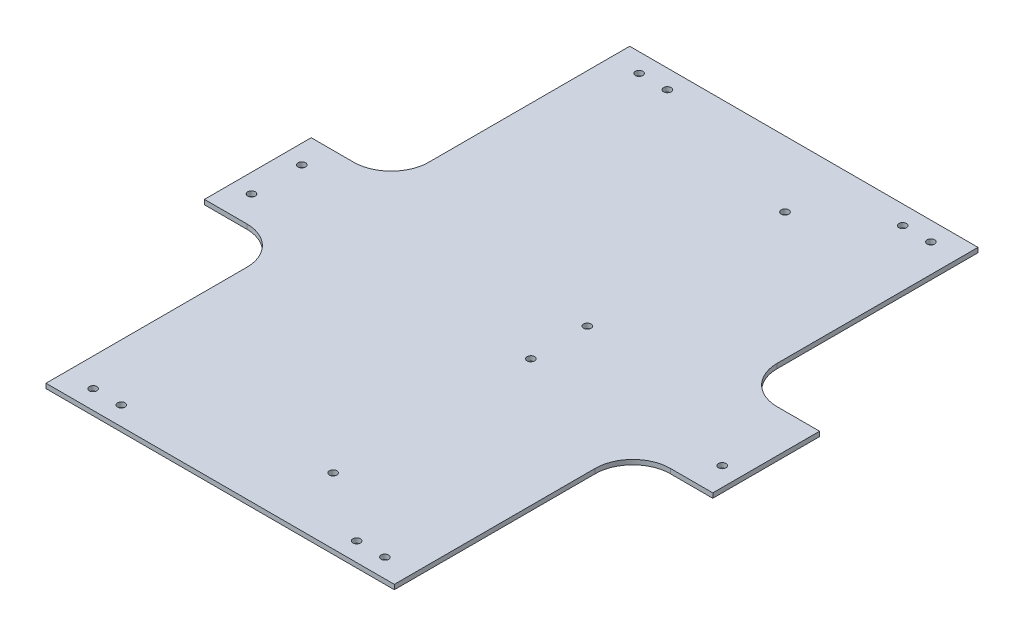
SolidWorks part; units mm, degrees
ref_plane "Front Plane" through (0, 0, 0) normal (0, 0, 1) x (1, 0, 0)
ref_plane "Top Plane" through (0, 0, 0) normal (0, 1, 0) x (1, 0, 0)
ref_plane "Right Plane" through (0, 0, 0) normal (1, 0, 0) x (0, 0, -1)
ref_plane "Plane1" through (0, -112.701, 0) normal (0, 1, 0) x (1, 0, 0)
sketch "Sketch2" plane through (0, -112.701, 0) normal (0, 1, 0) x (1, 0, 0)
  line L0 (-20.7168, -345.2625) -> (-228.5638, -345.2625) construction
  line L11 (271.4362, 21.4532) -> (186.4362, 21.4532)
  line L17 (186.4362, 274.7375) -> (-183.5638, 274.7375)
  line L20 (271.4362, 21.4532) -> (271.4362, -91.9782)
  line L21 (271.4362, -91.9782) -> (186.4362, -91.9782)
  line L24 (-268.5638, 21.4532) -> (-268.5638, -91.9782)
  line L25 (186.4362, 274.7375) -> (186.4362, 21.4532)
  line L26 (-20.7168, 274.7375) -> (-228.5638, 274.7375) construction
  line L27 (186.4362, -345.2625) -> (-183.5638, -345.2625)
  line L28 (271.4362, -35.2625) -> (-268.5638, -35.2625) construction
  line L30 (271.4362, -305.2625) -> (271.4362, 234.7375) construction
  line L31 (-268.5638, -305.2625) -> (-268.5638, 234.7375) construction
  line L44 (-183.5638, 274.7375) -> (-183.5638, 21.4532)
  line L45 (-183.5638, -91.9782) -> (-268.5638, -91.9782)
  line L46 (-183.5638, 21.4532) -> (-268.5638, 21.4532)
  line L47 (186.4362, -91.9782) -> (186.4362, -345.2625)
  line L48 (-183.5638, -91.9782) -> (-183.5638, -345.2625)
  line L49 (231.4362, -342.0925) -> (231.4362, -330.8925) construction
  line L50 (-228.5638, -330.8925) -> (-228.5638, -342.0925) construction
  line L51 (-265.3938, -96.9782) -> (-254.1938, -96.9782) construction
  line L52 (186.4362, -325.2625) -> (-183.5638, -325.2625) construction
  line L53 (-248.5638, -325.2625) -> (391.4362, -325.2625) construction
  line L54 (251.4362, 21.4532) -> (251.4362, -91.9782) construction
  line L55 (251.4362, 254.7375) -> (251.4362, -325.2625) construction
  line L56 (-248.5638, 21.4532) -> (-248.5638, -91.9782) construction
  line L57 (-248.5638, -325.2625) -> (-248.5638, 254.7375) construction
  line L58 (51.4362, 254.7375) -> (51.4362, -325.2625) construction
  line L59 (271.4362, -305.2625) -> (28.1987, -305.2625) construction
  circle A0 centre (156.4362, -325.2625) radius 4
  circle A1 centre (126.4362, -325.2625) radius 4
  circle A2 centre (251.4362, -61.9782) radius 4
  circle A4 centre (-153.5638, -325.2625) radius 4
  circle A5 centre (-123.5638, -325.2625) radius 4
  circle A6 centre (-248.5638, -61.9782) radius 4
  circle A7 centre (51.4362, -275.2625) radius 4
  circle A8 centre (51.4362, -65.2625) radius 4
  circle A9 centre (51.4362, -5.2625) radius 4
  circle A10 centre (51.4362, 204.7375) radius 4
  circle A11 centre (-248.5638, -8.5468) radius 4
  circle A12 centre (-123.5638, 254.7375) radius 4
  circle A13 centre (-153.5638, 254.7375) radius 4
  circle A14 centre (126.4362, 254.7375) radius 4
  circle A15 centre (156.4362, 254.7375) radius 4
  dimension "D3" = 5
  dimension "D5" = 30
  dimension "D4" = 8
  dimension "D1" = 45
  dimension "D2" = 45
  dimension "D6" = 30
  dimension "D7" = 30
  dimension "D8" = 30
  dimension "D9" = 30
  dimension "D10" = 30
  dimension "D11" = 30
  dimension "D12" = 30
extrude "Boss-Extrude1" add sketch "Sketch2" along normal blind 5
fillet "Fillet1" radius 40 4 edges at (-183.5638, -110.201, -21.4532) (186.4362, -110.201, -21.4532) (186.4362, -110.201, 91.9782) (-183.5638, -110.201, 91.9782)
